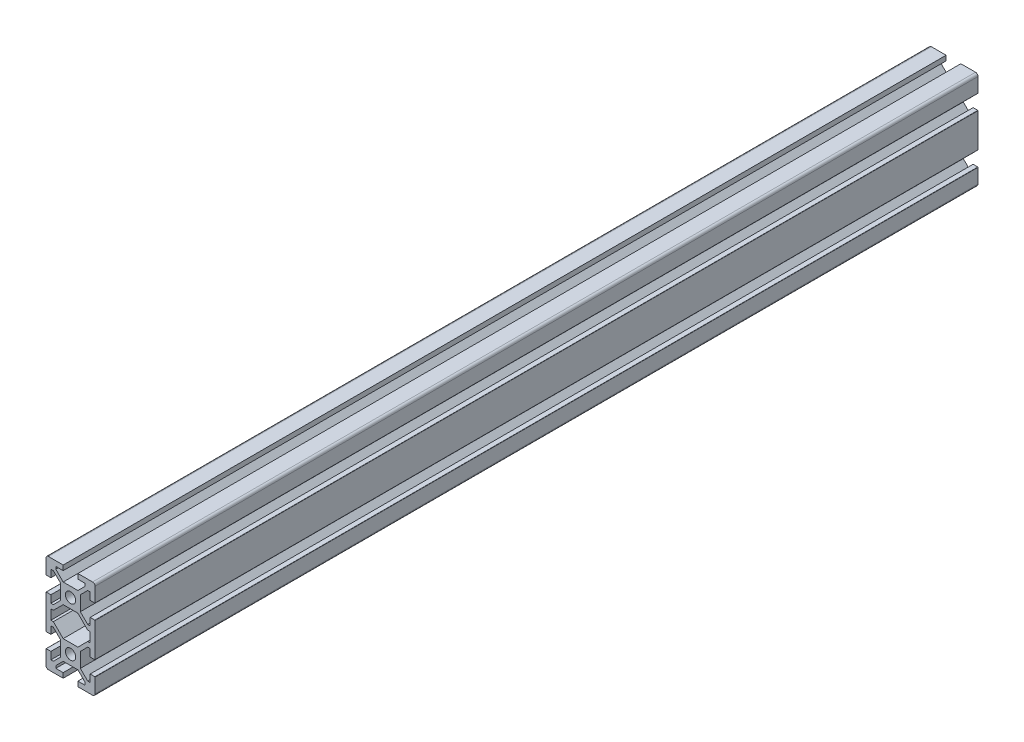
SolidWorks part; units mm, degrees
ref_plane "Front Plane" through (0, 0, 0) normal (0, 0, 1) x (1, 0, 0)
ref_plane "Top Plane" through (0, 0, 0) normal (0, 1, 0) x (1, 0, 0)
ref_plane "Right Plane" through (0, 0, 0) normal (1, 0, 0) x (0, 0, -1)
sketch "Sketch1" plane through (0, 0, 0) normal (0, 0, 1) x (1, 0, 0)
  line L0 (-7, -2) -> (-8, -2)
  line L1 (-8, -2) -> (-8, 2)
  line L2 (-8, 2) -> (-7, 2)
  line L3 (-7, 2) -> (-3, 6)
  line L4 (-3, 6) -> (3, 6)
  line L5 (3, 6) -> (7, 2)
  line L6 (7, 2) -> (8, 2)
  line L7 (8, 2) -> (8, -2)
  line L8 (8, -2) -> (7, -2)
  line L9 (7, -2) -> (3, -6)
  line L10 (3, -6) -> (-3, -6)
  line L11 (-3, -6) -> (-7, -2)
  line L12 (10, -19) -> (10, -13)
  line L13 (10, -13) -> (8, -13)
  line L14 (8, -13) -> (8, -16)
  line L15 (8, -16) -> (7, -16)
  line L16 (7, -16) -> (4, -13)
  line L17 (4, -13) -> (4, -7)
  line L18 (4, -7) -> (7, -4)
  line L19 (7, -4) -> (8, -4)
  line L20 (8, -4) -> (8, -7)
  line L21 (8, -7) -> (10, -7)
  line L22 (10, -7) -> (10, 7)
  line L23 (10, 7) -> (8, 7)
  line L24 (8, 7) -> (8, 4)
  line L25 (8, 4) -> (7, 4)
  line L26 (7, 4) -> (4, 7)
  line L27 (4, 7) -> (4, 13)
  line L28 (4, 13) -> (7, 16)
  line L29 (7, 16) -> (8, 16)
  line L30 (8, 16) -> (8, 13)
  line L31 (8, 13) -> (10, 13)
  line L32 (10, 13) -> (10, 19)
  line L33 (9, 20) -> (3, 20)
  line L34 (3, 20) -> (3, 18)
  line L35 (3, 18) -> (6, 18)
  line L36 (6, 18) -> (6, 17)
  line L37 (6, 17) -> (3, 14)
  line L38 (3, 14) -> (-3, 14)
  line L39 (-3, 14) -> (-6, 17)
  line L40 (-6, 17) -> (-6, 18)
  line L41 (-6, 18) -> (-3, 18)
  line L42 (-3, 18) -> (-3, 20)
  line L43 (-3, 20) -> (-9, 20)
  line L44 (-10, 19) -> (-10, 13)
  line L45 (-10, 13) -> (-8, 13)
  line L46 (-8, 13) -> (-8, 16)
  line L47 (-8, 16) -> (-7, 16)
  line L48 (-7, 16) -> (-4, 13)
  line L49 (-4, 13) -> (-4, 7)
  line L50 (-4, 7) -> (-7, 4)
  line L51 (-7, 4) -> (-8, 4)
  line L52 (-8, 4) -> (-8, 7)
  line L53 (-8, 7) -> (-10, 7)
  line L54 (-10, 7) -> (-10, -7)
  line L55 (-10, -7) -> (-8, -7)
  line L56 (-8, -7) -> (-8, -4)
  line L57 (-8, -4) -> (-7, -4)
  line L58 (-7, -4) -> (-4, -7)
  line L59 (-4, -7) -> (-4, -13)
  line L60 (-4, -13) -> (-7, -16)
  line L61 (-7, -16) -> (-8, -16)
  line L62 (-8, -16) -> (-8, -13)
  line L63 (-8, -13) -> (-10, -13)
  line L64 (-10, -13) -> (-10, -19)
  line L65 (-9, -20) -> (-3, -20)
  line L66 (-3, -20) -> (-3, -18)
  line L67 (-3, -18) -> (-6, -18)
  line L68 (-6, -18) -> (-6, -17)
  line L69 (-6, -17) -> (-3, -14)
  line L70 (-3, -14) -> (3, -14)
  line L71 (3, -14) -> (6, -17)
  line L72 (6, -17) -> (6, -18)
  line L73 (6, -18) -> (3, -18)
  line L74 (3, -18) -> (3, -20)
  line L75 (3, -20) -> (9, -20)
  line L76 (-8, 0) -> (0, 0) construction
  line L77 (0, 0) -> (8, 0) construction
  line L78 (0, 6) -> (0, 0) construction
  line L79 (0, 0) -> (0, -6) construction
  circle A0 centre (0, -10) radius 2.1
  circle A1 centre (0, 10) radius 2.1
  arc A2 (9, -20) -> (10, -19) centre (9, -19) ccw
  arc A3 (10, 19) -> (9, 20) centre (9, 19) ccw
  arc A4 (-9, 20) -> (-10, 19) centre (-9, 19) ccw
  arc A5 (-10, -19) -> (-9, -20) centre (-9, -19) ccw
  dimension "D1" = 40
  dimension "D2" = 20
extrude "Boss-Extrude1" add sketch "Sketch1" against normal blind 360
fillet "Fillet1" radius 0.1 8 edges at (10, -13, -180) (10, -7, -180) (10, 7, -180) (10, 13, -180) (-10, 13, -180) (-10, -13, -180) (-10, -7, -180) (-10, 7, -180)
